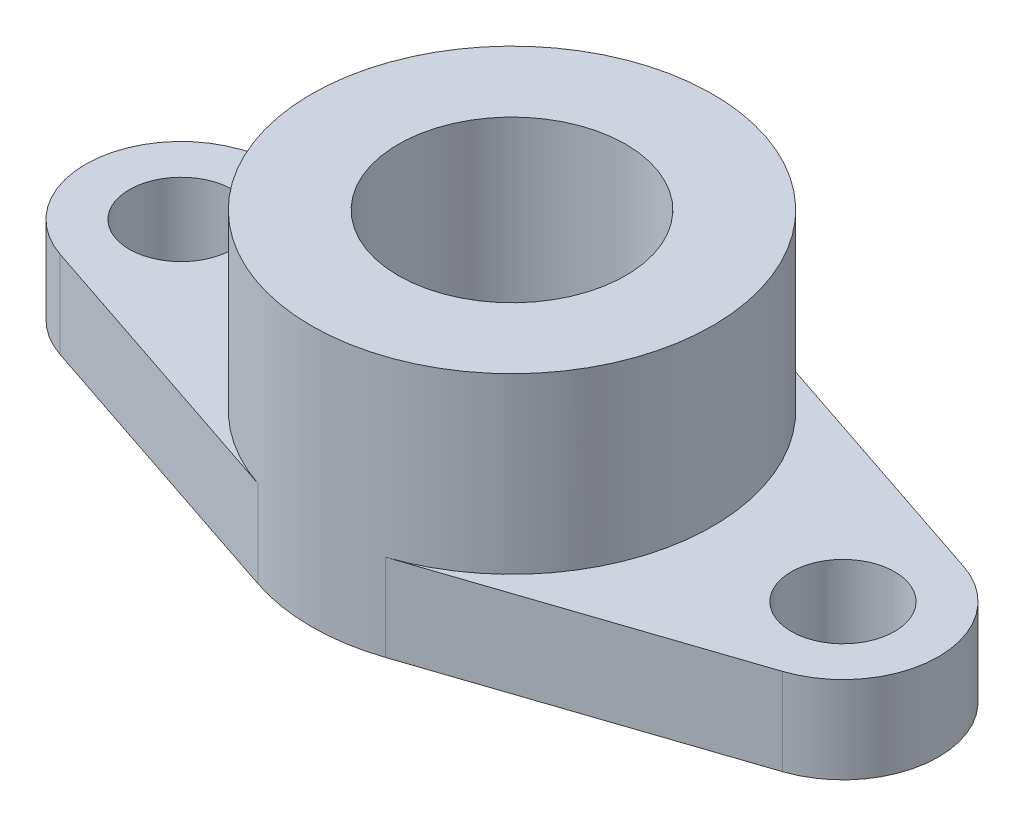
SolidWorks part; units mm, degrees
ref_plane "Front Plane" through (0, 0, 0) normal (0, 0, 1) x (1, 0, 0)
ref_plane "Top Plane" through (0, 0, 0) normal (0, 1, 0) x (1, 0, 0)
ref_plane "Right Plane" through (0, 0, 0) normal (1, 0, 0) x (0, 0, -1)
sketch "Sketch1" plane through (0, 0, 0) normal (0, 1, 0) x (1, 0, 0)
  line L0 (0, 0) -> (6.5484, 0) construction
  line L1 (0, 0) -> (19.05, 0) construction
  line L2 (20.7963, 5.2154) -> (3.6667, 10.9509)
  line L3 (3.6667, -10.9509) -> (20.7963, -5.2154)
  line L4 (0, 0) -> (-19.05, 0) construction
  line L5 (-20.7963, 5.2154) -> (-3.6667, 10.9509)
  line L6 (-20.7963, -5.2154) -> (-3.6667, -10.9509)
  circle A0 centre (0, 0) radius 4.826
  circle A1 centre (0, 0) radius 6.5484 construction
  arc A2 (3.6667, 10.9509) -> (3.6667, -10.9509) centre (0, 0) ccw construction
  circle A3 centre (19.05, 0) radius 2.9766
  arc A4 (20.7963, -5.2154) -> (20.7963, 5.2154) centre (19.05, 0) ccw
  circle A5 centre (0, 0) radius 11.5484 construction
  circle A6 centre (-19.05, 0) radius 2.9766
  arc A7 (-20.7963, 5.2154) -> (-20.7963, -5.2154) centre (-19.05, 0) ccw
  arc A10 (-3.6667, -10.9509) -> (3.6667, -10.9509) centre (0, 0) ccw
  arc A11 (3.6667, 10.9509) -> (-3.6667, 10.9509) centre (0, 0) ccw
  dimension "D1" = 9.652
  dimension "D2" = 13.0969
  dimension "D3" = 23.0969
  dimension "D5" = 5.9531
  dimension "D7" = 5.9531
  dimension "D6" = 5.5
  dimension "D4" = 19.05
  dimension "D8" = 19.05
extrude "Boss-Extrude1" add sketch "Sketch1" along normal blind 5
sketch "Sketch2" plane through (0, 5, 0) normal (0, 1, 0) x (1, 0, 0)
  circle A0 centre (0, 0) radius 11.5484
  arc A1 (-3.6667, -10.9509) -> (3.6667, -10.9509) centre (0, 0) ccw construction
  circle A2 centre (0, 0) radius 6.5484
  dimension "D1" = 13.0969
extrude "Boss-Extrude2" add sketch "Sketch2" along normal blind 10
equation "\"z\" = 8\t\t\t\t'number of blades"
equation "\"de\" = 0.43in\t\t\t'entrance eye diameter"
equation "\"de_length\" = 10mm\t\t'entrance eye consistent length"
equation "\"d_exit\" = 0.18in \t\t'throat aka d1"
equation "\"d2\" = 2.1in \t\t\t'outer diameter of the impeller"
equation "\"b2\" = .2in\t\t\t'tip height from disc surface at d2; slightly higher than d_exit"
equation "\"b1\" = \"b2\" + (\"d2\"/2 - \"de\"/2)*tan(\"theta\") \t\t\t'tip height from disc surface at inlet eye"
equation "\"theta\" = 12\t\t\t'angle of blades from inner to outer "
equation "\"ae\" = 3.14*(\"de\"^2)/4\t\t'entrance eye area'"
equation "\"ce\" = 3.14*\"de\"\t\t'entrance eye circumference"
equation "\"av_ratio\" = .325\t\t'ratio of av/ae at N_s of 470, range is .275 to .375, .325 ideal. High ratio means bigger area means smaller blades"
equation "\"av\" = \"ae\"*\"av_ratio\"\t\t'area between just two blades"
equation "\"s_open\" = \"av\"/\"b1\"\t\t'width of open area"
equation "\"s\"=\"ce\" - \"z\"*\"s_open\""
equation "\"min blade thickness\" = .15in"
equation "\"bearing OD\" = 30mm"
equation "\"bearing ID\"= 10mm"
equation "\"bearing depth\"= 9mm"
equation "\"bearing outer race thickness\"= 1mm"
equation "\"bearing inner race thickness\"= 1mm"
equation "\"bearing bore\" = \"bearing depth\" + 1mm"
equation "\"lower seal OD\" = .917in\t\t'this is https://www.mcmaster.com/#9281k121/=174001b"
equation "\"lower seal ID\"= .375in"
equation "\"lower seal depth\" = .625in + .218in"
equation "\"lower seal bore\" = \"lower seal depth\" + 1mm"
equation "\"upper seal OD\" = 1.125in\t'this is https://www.mcmaster.com/#5154t33/=173zuau, needs to be visually inspected before machining!"
equation "\"upper seal ID\"= 0.625in"
equation "\"upper seal depth\"= .25in\t'aka height; these values need to be confirmed by inspection!! We may want to compress the height."
equation "\"upper seal bore\" = \"upper seal depth\" + 1mm"
equation "\"big o-ring thickness\" = .139in"
equation "\"big o-ring OD\" = 2.734in"
equation "\"big o-ring ID\" = 3.012in"
equation "\"big o-ring groove depth\" = \"big o-ring thickness\"*4/5"
equation "\"impeller center height\" = \"impeller base thickness\" + \"b1\"\t'impeller height at de"
equation "\"impeller outer height\" = \"impeller base thickness\" + \"b2\"\t'impeller height at de"
equation "\"impeller upper clearance\"= .5mm"
equation "\"impeller horizontal clearance\"= (\"d2\"*1.15 - \"d2\")/2 \t\t'clearance based on D2-D3 ratio for circular volute, ranges 1.15 to 1.2"
equation "\"impeller bottom clearance\"= .5mm"
equation "\"impeller base thickness\"= 2mm"
equation "\"impeller dowel diameter\" = 2mm"
equation "\"impeller bolt head diameter\" = \"m4 head bore diameter\""
equation "\"impeller bolt head depth\" = 4mm"
equation "\"impeller bolt stop depth\" = 3mm"
equation "\"impeller bolt bore\" = \"m4 clearance\""
equation "\"impeller shaft bore depth\" = 12mm"
equation "\"impeller shaft bore\" = 8mm"
equation "\"impeller boss depth\" = \"impeller shaft bore depth\"+\"impeller bolt stop depth\"+\"impeller bolt head depth\"-\"impeller base thickness\""
equation "\"impeller boss diameter\" = \"upper seal ID\""
equation "\"impeller dowel length\" = 2mm*2 + \"impeller shaft bore\""
equation "\"coupler motor shaft hole ID\"= 8mm"
equation "\"coupler OD\"= 17mm"
equation "\"coupler length\"= 25mm"
equation "\"motor OD\" = 64mm"
equation "\"motor shaft diameter\"= 8mm"
equation "\"motor shaft pride\"= 32mm"
equation "\"motor to bearing plate distance\" = \"motor shaft pride\" + 2mm +\"coupler length\"/2"
equation "\"square plate bolt bore\" = \"m8 clearance\""
equation "\"square plate bolt head diameter\" = 13.5mm"
equation "\"square plate bolt head depth\" = 8mm"
equation "\"square plate bolt pattern diameter\"= 3.5in"
equation "\"motor mount center bore\"= \"coupler OD\"+ 4mm"
equation "\"motor mount post radius\"= ( 3 * \"square plate bolt bore\" ) / 2"
equation "\"motor mount m4 screw hole diameter\"= 4mm"
equation "\"motor mount m4 head diameter\"= 7.25mm"
equation "\"motor mount m4 head depth\"= 4mm"
equation "\"motor mount m4 pattern diamater\" = 30mm"
equation "\"motor mount plate thickness\"= 8mm + \"motor mount m4 head depth\""
equation "\"bearing plate stop ID\" = \"bearing OD\" - 4mm"
equation "\"bearing plate stop depth\" = 3mm"
equation "\"bearing plate thickness\" = \"bearing bore\" + \"bearing plate stop depth\" + \"shaft bearing stop length\""
equation "\"lower seal plate lip depth\" = 2mm"
equation "\"lower seal plate lip ID\" = \"lower seal OD\" - 3mm"
equation "\"lower seal plate thickness\" = \"lower seal plate lip depth\" + \"lower seal bore\""
equation "\"shaft coupler section diameter\" = 8mm"
equation "\"shaft coupler section length\" = \"motor to bearing plate distance\" - \"motor shaft pride\" - 2mm"
equation "\"shaft bearing section diameter\" = \"bearing ID\""
equation "\"shaft bearing section length\" = \"bearing plate stop depth\" + \"bearing depth\""
equation "\"shaft bearing stop diameter\" = \"bearing ID\" + 4mm"
equation "\"shaft bearing stop length\" = 3mm"
equation "\"shaft lower seal section diameter\" = \"lower seal ID\""
equation "\"shaft lower seal section length\" = \"lower seal plate thickness\" + 1mm"
equation "\"shaft impeller section diameter\" = \"impeller shaft bore\""
equation "\"shaft impeller section length\" = \"upper seal plate thickness\" + \"upper seal plate riser\" + \"impeller bottom clearance\" + \"impeller base thickness\" - \"impeller bolt head depth\" - \"impeller bolt stop depth\""
equation "\"upper seal plate thickness\" = \"upper seal plate pressure hole diameter\"+10mm"
equation "\"upper seal plate lip ID\" = \"upper seal OD\" - 3mm"
equation "\"upper seal plate riser\" = 6.59mm \t\t'this number needs to be read from the housing file"
equation "\"upper seal plate pressure hole diameter\" = .125in\t'this is 1/8 drill "
equation "\"upper seal plate pressure tap diameter\" = .328125in \t'this is 21/64 drill for a 1/8 ANPT tap"
equation "\"upper seal plate pressure tap grip\" = 5mm\t\t'this is the area around the tap so it doesn't crack"
equation "\"upper seal plate pressure tap depth\" = 12"
equation "\"impeller cavity center height\"= \"impeller bottom clearance\" + \"impeller upper clearance\" + \"impeller center height\""
equation "\"impeller cavity diameter\"= 2 * \"impeller horizontal clearance\" + \"d2\" \t\t\t\t\t\t\t\t\t'called D3 analytically"
equation "\"impeller cavity outer height\"= \"impeller bottom clearance\" + \"impeller upper clearance\" + \"impeller base thickness\" + \"b2\" \t\t'this is height at impeller diameter d2, not at d3"
equation "\"impeller housing thickness\"= \"impeller housing exit threaded diameter\" + 2*\"impeller housing outlet grip\""
equation "\"impeller housing diameter\" = \"square plate bolt pattern diameter\" + 2*\"motor mount post radius\""
equation "\"impeller housing bolt count\" = 8"
equation "\"impeller housing bolt diameter\" = \"m6 clearance\""
equation "\"impeller housing bolt pattern diameter\" = 3.5in"
equation "\"impeller housing threaded inlet diameter\" = 0.515625in \t'this is the 33/64 drill size for 9/16-18 fitting, expecting swagelok SS-8FK0-1-6STH fitting"
equation "\"impeller housing threaded inlet depth\"= 10mm"
equation "\"impeller housing exit threaded diameter\"= 0.515625in \t\t'this is the 33/64 drill size for 9/16-18 fitting, expecting swagelok SS-8FK0-1-6STH fitting"
equation "\"impeller housing exit threaded depth\"= 10mm"
equation "\"impeller housing diffuser conical angle\"=10"
equation "\"impeller housing diffuser tangent angle\"=5"
equation "\"impeller housing diffuser final diameter\" = .38in\t\t'aka d2'"
equation "\"impeller housing outlet grip\" = 5mm"
equation "\"end mill size\" = 0.375in\t'for 3/8 endmill"
equation "\"m4 clearance\" = 0.171875in \t'this is 11/64 bit for 4.36mm"
equation "\"m4 tap\" = 0.125in\t\t'this is 1/8 bit for 3.17mm"
equation "\"m4 head bore diameter\" = 7.5mm"
equation "\"m4 head bore depth\" = 5mm\t'actual is ~4mm"
equation "\"m6 clearance\" = 0.234375in\t'this is 15/64 bit = 5.95mm, could use 6mm bit, B bit for 6.04mm or 1/4 bit for 6.35mm"
equation "\"m6 tap\" = 5mm\t\t\t'5mm is appropriate, could use 13/64 or #5,6,7"
equation "\"m6 head bore diameter\" = 11mm\t\t"
equation "\"m6 head bore depth\" = 7mm\t'actual is 6mm"
equation "\"m8 clearance\" = 0.3125in\t'this is 5/16in for 7.93mm, could use 8mm, O,P, or 21/64"
equation "\"m8 tap\" = 0.265625in\t\t'this is 17/64 for 6.746875mm"
equation "\"m8 head bore diameter\" = 14mm"
equation "\"m8 head bore depth\" = 9mm\t'actual is 8mm"
equation "\"D1@Sketch1\"=\"impeller housing diffuser final diameter\""
equation "\"D2@Sketch1\"=\"impeller housing exit threaded diameter\""
equation "\"D3@Sketch1\"=\"impeller housing exit threaded diameter\"+\"impeller housing outlet grip\"*2 "
equation "\"D5@Sketch1\"=\"m6 clearance\""
equation "\"D7@Sketch1\"=\"m6 clearance\""
equation "\"D6@Sketch1\"=\"m6 head bore diameter\"/2"
equation "\"D1@Sketch2\"=\"impeller housing exit threaded diameter\""
equation "\"D1@Boss-Extrude2\"=10mm"
equation "\"diffuser cartridge OD\" =.75in"
equation "\"diffuser flange bolt pattern diameter\" = 1.5in"
equation "\"D4@Sketch1\"=\"diffuser flange bolt pattern diameter\"/2"
equation "\"D8@Sketch1\"=\"diffuser flange bolt pattern diameter\"/2"
